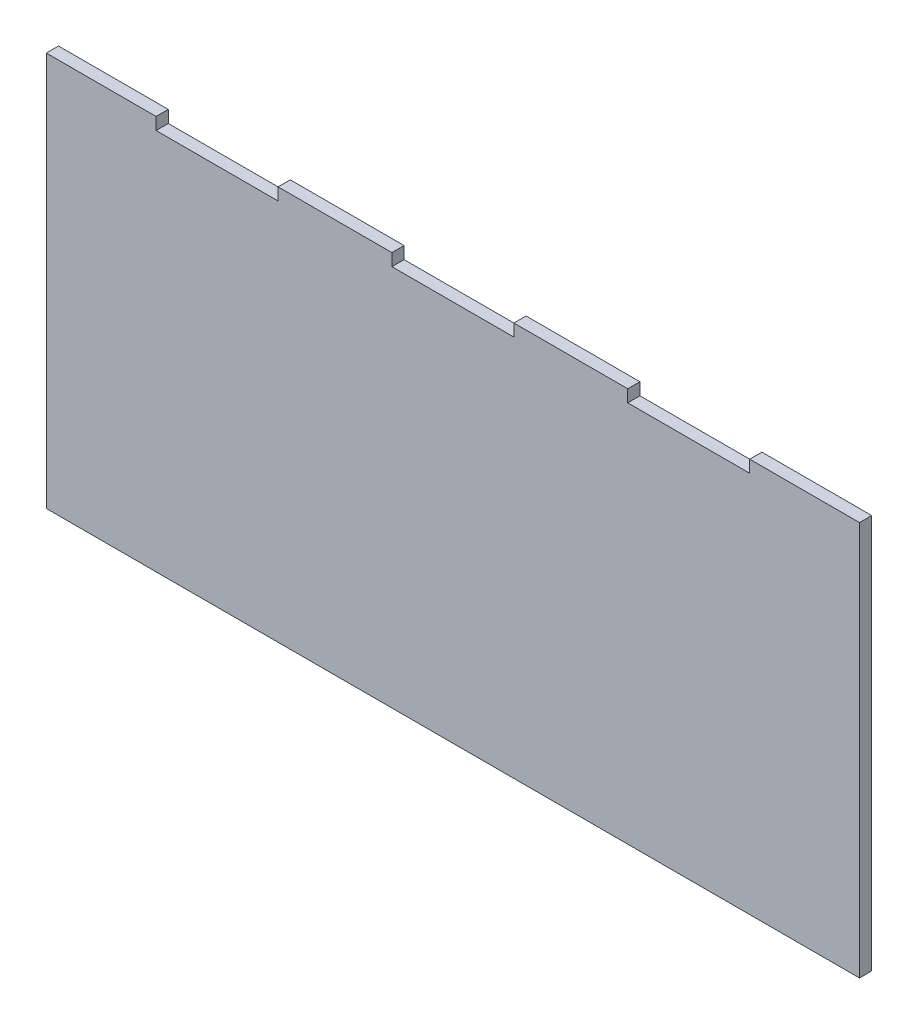
SolidWorks part; units mm, degrees
ref_plane "前基準面" through (0, 0, 0) normal (0, 0, 1) x (1, 0, 0)
ref_plane "上基準面" through (0, 0, 0) normal (0, 1, 0) x (1, 0, 0)
ref_plane "右基準面" through (0, 0, 0) normal (1, 0, 0) x (0, 0, -1)
sketch "草圖1" plane through (0, 0, 0) normal (0, 0, 1) x (1, 0, 0)
  line L1 (-96, 139.0705) -> (-69, 139.0705)
  line L2 (-96, 139.0705) -> (-96, 42.0705)
  line L4 (104, 139.0705) -> (104, 42.0705)
  line L12 (-39, 139.0705) -> (-11, 139.0705)
  line L17 (19, 139.0705) -> (47, 139.0705)
  line L18 (77, 139.0705) -> (104, 139.0705)
  line L30 (-11, 139.0705) -> (-11, 136.0705)
  line L32 (-69, 139.0705) -> (-69, 136.0705)
  line L33 (-69, 136.0705) -> (-39, 136.0705)
  line L34 (-39, 139.0705) -> (-39, 136.0705)
  line L36 (19, 139.0705) -> (19, 136.0705)
  line L37 (-11, 136.0705) -> (19, 136.0705)
  line L38 (47, 139.0705) -> (47, 136.0705)
  line L40 (77, 139.0705) -> (77, 136.0705)
  line L41 (47, 136.0705) -> (77, 136.0705)
  line L47 (-96, 42.0705) -> (104, 42.0705)
  dimension "D16" = 27
  dimension "D17" = 30
  dimension "D18" = 3
  dimension "D20" = 27
  dimension "D19" = 3
extrude "填料-伸長1" add sketch "草圖1" along normal blind 3
